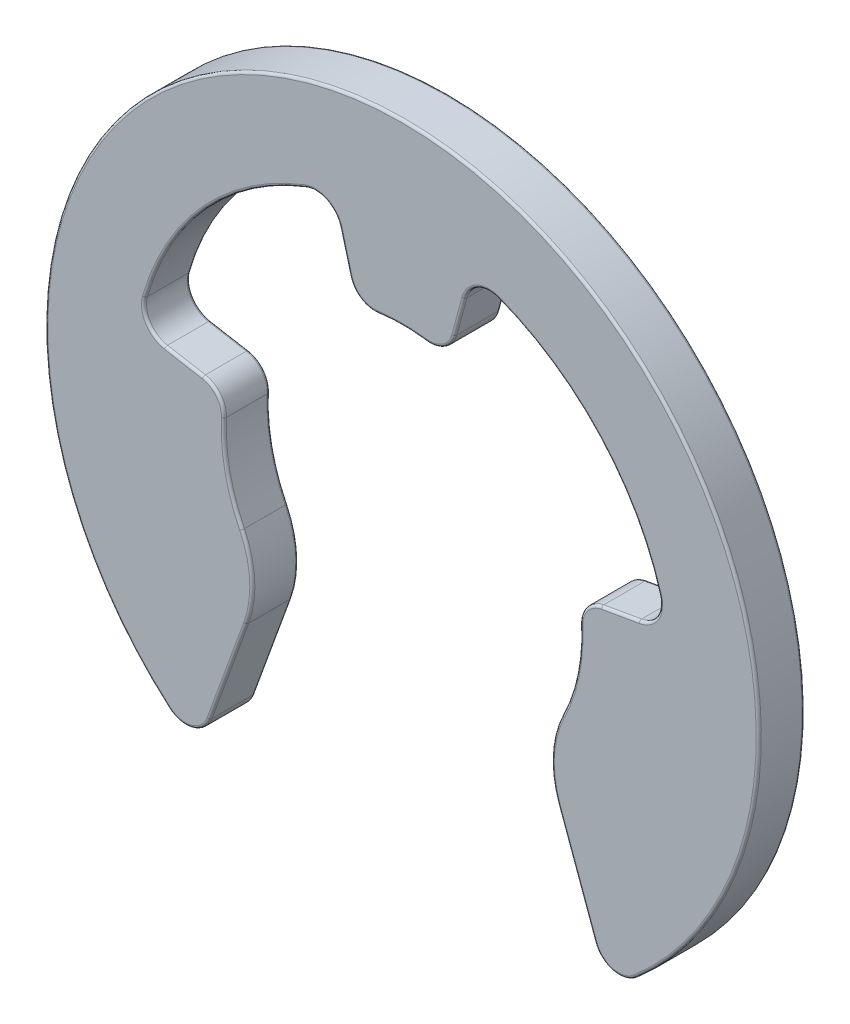
SolidWorks part; units mm, degrees
material "AISI 304"
ref_plane "前视基准面" through (0, 0, 0) normal (0, 0, 1) x (1, 0, 0)
ref_plane "上视基准面" through (0, 0, 0) normal (0, 1, 0) x (1, 0, 0)
ref_plane "右视基准面" through (0, 0, 0) normal (1, 0, 0) x (0, 0, -1)
sketch "草图1" plane through (0, 0, 0) normal (0, 0, 1) x (1, 0, 0)
  line L0 (-3.0586, -3.1062) -> (-3.7803, -5.089)
  line L1 (0, 8.3114) -> (0, -7.8543) construction
  line L2 (3.0586, -3.1062) -> (3.7803, -5.089)
  line L3 (-3.9083, 0.6891) -> (-4.6518, 0.8202)
  line L4 (-1.0272, 3.8334) -> (-1.2226, 4.5627)
  line L5 (-9.3078, 0) -> (10.6777, 0) construction
  line L6 (3.9083, 0.6891) -> (4.6518, 0.8202)
  line L7 (1.0272, 3.8334) -> (1.2226, 4.5627)
  arc A0 (3.1423, -1.5414) -> (3.4958, 0.1721) centre (0, 0) ccw
  arc A1 (4.577, -5.2963) -> (-4.577, -5.2963) centre (0, 0) ccw
  arc A3 (-1.8851, 4.8999) -> (-5.0456, 1.4508) centre (0, 0) ccw
  arc A4 (5.0456, 1.4508) -> (1.8851, 4.8999) centre (0, 0) ccw
  arc A5 (-3.4958, 0.1721) -> (-3.1423, -1.5414) centre (0, 0) ccw
  arc A6 (0.4762, 3.4675) -> (-0.4762, 3.4675) centre (0, 0) ccw
  arc A7 (3.7803, -5.089) -> (4.577, -5.2963) centre (4.2501, -4.918) ccw
  arc A8 (-3.7803, -5.089) -> (-4.577, -5.2963) centre (-4.2501, -4.918) cw
  arc A9 (-4.6518, 0.8202) -> (-5.0456, 1.4508) centre (-4.565, 1.3127) cw
  arc A10 (-3.4958, 0.1721) -> (-3.9083, 0.6891) centre (-3.9952, 0.1967) ccw
  arc A11 (3.4958, 0.1721) -> (3.9083, 0.6891) centre (3.9952, 0.1967) cw
  arc A12 (4.6518, 0.8202) -> (5.0456, 1.4508) centre (4.565, 1.3127) ccw
  arc A13 (1.8851, 4.8999) -> (1.2226, 4.5627) centre (1.7055, 4.4332) ccw
  arc A14 (0.4762, 3.4675) -> (1.0272, 3.8334) centre (0.5442, 3.9628) ccw
  arc A15 (-1.0272, 3.8334) -> (-0.4762, 3.4675) centre (-0.5442, 3.9628) ccw
  arc A16 (-1.2226, 4.5627) -> (-1.8851, 4.8999) centre (-1.7055, 4.4332) ccw
  arc A17 (3.0586, -3.1062) -> (3.1423, -1.5414) centre (4.9379, -2.4221) cw
  arc A18 (-3.0586, -3.1062) -> (-3.1423, -1.5414) centre (-4.9379, -2.4221) ccw
  point P20 (4.015, -5.7341)
  point P23 (-4.015, -5.7341)
  point P26 (-5.1702, 0.9117)
  point P29 (-3.4468, 0.6078)
  point P32 (3.4468, 0.6078)
  point P35 (5.1702, 0.9117)
  point P38 (1.3588, 5.0711)
  point P41 (0.9059, 3.3807)
  point P44 (-0.9059, 3.3807)
  point P47 (-1.3588, 5.0711)
  point P50 (2.7267, -2.1944)
  point P53 (-2.7267, -2.1944)
  dimension "D1" = 7
  dimension "D2" = 14
  dimension "D7" = 5.25
  dimension "D10" = 1.75
  dimension "D14" = 0.5
  dimension "D15" = 2
  dimension "D3" = 20
  dimension "D4" = 3.7669
  dimension "D5" = 20
  dimension "D6" = 3.7669
  dimension "D8" = 10
  dimension "D9" = 15
  dimension "D11" = 1.75
  dimension "D12" = 1.75
  dimension "D13" = 1.75
extrude "凸台-拉伸1" add sketch "草图1" along normal blind 0.9
fillet "圆角1" radius 0.05 48 edges at (1.4787, 4.8788, 0) (1.1249, 4.198, 0) (0.8208, 3.5463, 0) (0, 3.5, 0) (-0.8208, 3.5463, 0) (-1.1249, 4.198, 0) (-1.4787, 4.8788, 0) (-3.8707, 3.5468, 0) (-4.9891, 1.0478, 0) (-4.2801, 0.7547, 0) (-3.6043, 0.5086, 0) (-3.4278, -0.707, 0) (-2.9408, -2.3152, 0) (-3.4194, -4.0976, 0) (-4.1242, -5.4019, 0) (0, 7, 0) (4.1242, -5.4019, 0) (3.4194, -4.0976, 0) (2.9408, -2.3152, 0) (3.4278, -0.707, 0) (3.6043, 0.5086, 0) (4.2801, 0.7547, 0) (4.9891, 1.0478, 0) (-4.9891, 1.0478, 0.9) (-4.2801, 0.7547, 0.9) (-3.6043, 0.5086, 0.9) (-3.4278, -0.707, 0.9) (-2.9408, -2.3152, 0.9) (-3.4194, -4.0976, 0.9) (-4.1242, -5.4019, 0.9) (0, 7, 0.9) (4.1242, -5.4019, 0.9) (3.4194, -4.0976, 0.9) (2.9408, -2.3152, 0.9) (3.4278, -0.707, 0.9) (3.6043, 0.5086, 0.9) (4.2801, 0.7547, 0.9) (4.9891, 1.0478, 0.9) (3.8707, 3.5468, 0.9) (1.4787, 4.8788, 0.9) (1.1249, 4.198, 0.9) (0.8208, 3.5463, 0.9) (0, 3.5, 0.9) (-0.8208, 3.5463, 0.9) (-1.1249, 4.198, 0.9) (-1.4787, 4.8788, 0.9) (3.8707, 3.5468, 0) (-3.8707, 3.5468, 0.9)
